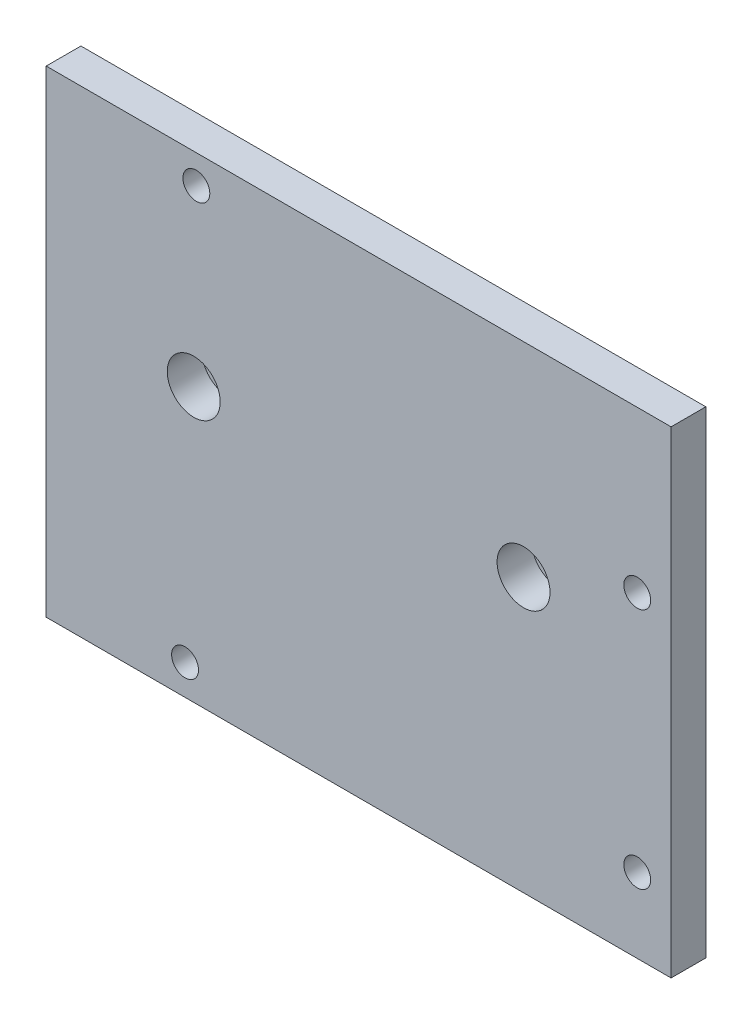
SolidWorks part; units mm, degrees
ref_plane "Front" through (0, 0, 0) normal (0, 0, 1) x (1, 0, 0)
ref_plane "Top" through (0, 0, 0) normal (0, 1, 0) x (1, 0, 0)
ref_plane "Right" through (0, 0, 0) normal (1, 0, 0) x (0, 0, -1)
sketch "Sketch1" plane through (0, 0, 0) normal (0, 0, 1) x (1, 0, 0)
  line L1 (-29, -6) -> (29, -6)
  line L2 (-29, -6) -> (-29, 6)
  line L3 (-29, 6) -> (29, 6)
  line L4 (29, -6) -> (29, 6)
  line L5 (-29, -6) -> (29, 6) construction
  line L6 (-29, 6) -> (29, -6) construction
  circle A0 centre (-19, 0) radius 1.55
  circle A1 centre (19, 0) radius 1.55
  point P0 (0, 0)
  dimension "D3" = 3.1
  dimension "D4" = 3.1
  dimension "D6" = 38
  dimension "D1" = 12
  dimension "D2" = 58
  dimension "D5" = 10
extrude "Boss-Extrude1" add sketch "Sketch1" along normal blind 6
sketch "Sketch2" plane through (0, 0, 6) normal (0, 0, 1) x (1, 0, 0)
  line L4 (29, -6) -> (29, 6)
  line L5 (29, 6) -> (-29, 6)
  line L6 (-29, 6) -> (-29, -6)
  line L7 (-29, -6) -> (29, -6)
  line L8 (29, -6) -> (29, 6)
  line L9 (29, 6) -> (-29, 6)
  line L10 (-29, 6) -> (-29, -6)
  line L11 (-29, -6) -> (29, -6)
  line L13 (-36, 23.5) -> (36, 23.5)
  line L14 (-36, 23.5) -> (-36, -31.5)
  line L15 (-36, -31.5) -> (36, -31.5)
  line L16 (36, 23.5) -> (36, -31.5)
  line L17 (-36, 23.5) -> (36, -31.5) construction
  line L18 (-36, -31.5) -> (36, 23.5) construction
  circle A0 centre (19, 0) radius 1.55 construction
  circle A1 centre (-19, 0) radius 1.55 construction
  circle A2 centre (19, 0) radius 1.55 construction
  circle A3 centre (-19, 0) radius 1.55 construction
  circle A4 centre (32.1, 5) radius 1.55
  circle A5 centre (-20, -28) radius 1.55
  circle A6 centre (-18.7, 20.2) radius 1.55
  circle A7 centre (32.1, -22.9) radius 1.55
  circle A8 centre (-19, 0) radius 3.05
  circle A9 centre (19, 0) radius 3.05
  point P10 (0, -4)
  line M15 (29, -6) -> (29, 6)
  line M16 (29, 6) -> (-29, 6)
  line M17 (-29, 6) -> (-29, -6)
  line M18 (-29, -6) -> (29, -6)
  circle M19 centre (-19, 0) radius 1.55
  circle M20 centre (19, 0) radius 1.55
  dimension "D3" = 3.1
  dimension "D4" = 3.1
  dimension "D5" = 52.1
  dimension "D6" = 33
  dimension "D8" = 28
  dimension "D12" = 3.1
  dimension "D13" = 48.2
  dimension "D15" = 3.1
  dimension "D16" = 27.9
  dimension "D17" = 6.1
  dimension "D18" = 6.1
  dimension "D2" = 55
  dimension "D7" = 1
  dimension "D9" = 72
  dimension "D10" = 16
  dimension "D11" = 3.5
  dimension "D14" = 17.3
  dimension "D1" = 0
extrude "Boss-Extrude2" add sketch "Sketch2" along normal blind 4 contours L16 L13 L14 L15 A7 A6 A5 A4 M15 M18 M17 M16 | M18 M15 M16 M17 M19 M20
